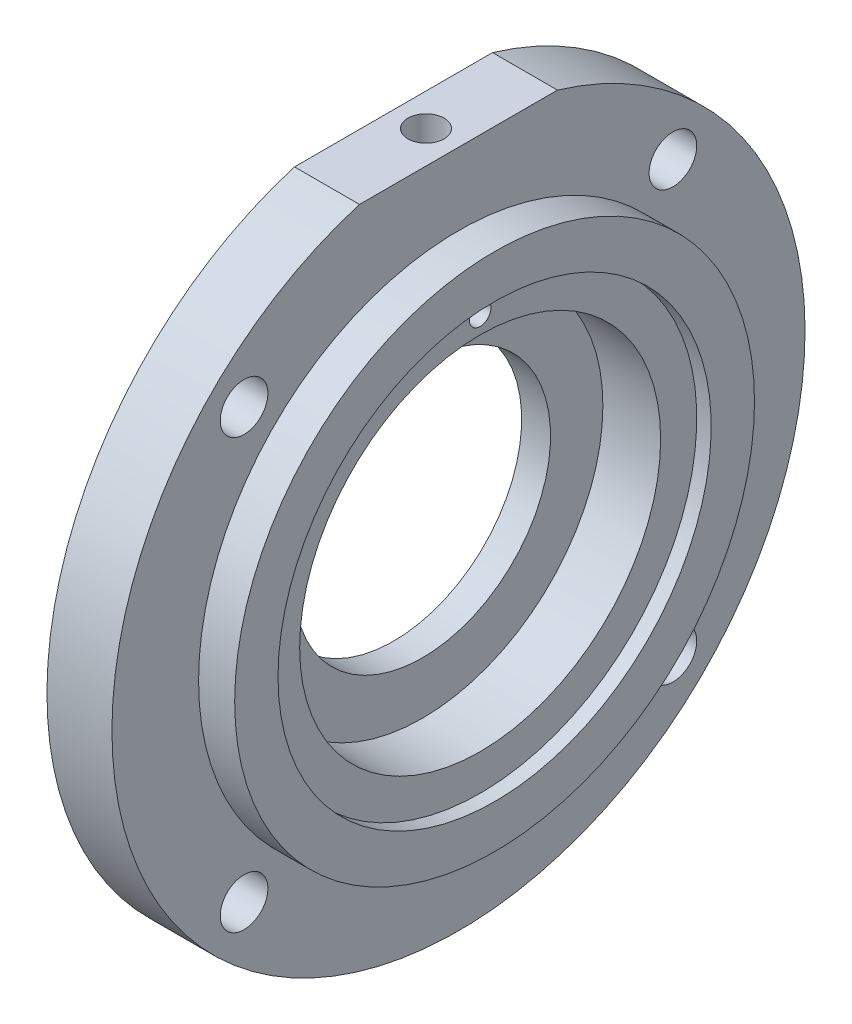
SolidWorks part; units mm, degrees
ref_plane "Front Plane" through (0, 0, 0) normal (0, 0, 1) x (1, 0, 0)
ref_plane "Top Plane" through (0, 0, 0) normal (0, 1, 0) x (1, 0, 0)
ref_plane "Right Plane" through (0, 0, 0) normal (1, 0, 0) x (0, 0, -1)
sketch "Sketch1" plane through (0, 0, 0) normal (0, 0, 1) x (1, 0, 0)
  line L0 (0, 0) -> (14, 0) construction
  line L1 (0, 48) -> (0, 17.75)
  line L2 (0, 17.75) -> (4, 17.75)
  line L3 (4, 17.75) -> (4, 25)
  line L4 (4, 25) -> (12, 25)
  line L5 (12, 25) -> (12, 30)
  line L6 (12, 30) -> (14, 30)
  line L7 (14, 30) -> (14, 36)
  line L8 (14, 36) -> (9, 36)
  line L9 (9, 36) -> (9, 48)
  line L10 (9, 48) -> (0, 48)
  point P13 (0, 0)
  point P15 (0, 55.9334)
  dimension "D1" = 14
  dimension "D2" = 35.5
  dimension "D3" = 4
  dimension "D4" = 2
  dimension "D5" = 5
  dimension "D6" = 50
  dimension "D7" = 60
  dimension "D8" = 72
  dimension "D9" = 96
revolve "Revolve1" add sketch "Sketch1" angle 360 about L0
sketch "Sketch2" plane through (0, 0, 0) normal (1, 0, 0) x (0, 0, -1)
  line L1 (-13.7113, 48) -> (13.7113, 48)
  line L2 (-13.7113, 48) -> (-13.7113, 46)
  line L3 (-13.7113, 46) -> (13.7113, 46)
  line L4 (13.7113, 48) -> (13.7113, 46)
  circle A0 centre (0, 0) radius 48 construction
  point P5 (0, 48)
  point P6 (0, 0)
  dimension "D1" = 46
extrude "Cut-Extrude1" cut sketch "Sketch2" along normal through all
hole_wizard "M6x1.0 Tapped Hole1" positions "Sketch5" profile "Sketch6" tap size "M6x1.0" standard "ANSI Metric"
sketch "Sketch5" plane through (0, 46, 0) normal (0, 1, 0) x (1, 0, 0)
  line L0 (0, 0) -> (9, 0) construction
  line L1 (9, -13.7113) -> (9, 13.7113) construction
  point P0 (4.5, 0)
  point P8 (0, 0)
  point P9 (4.5, 0)
sketch "Sketch6" plane through (4.5, 46, 0) normal (1, 0, 0) x (0, 0, 1)
  line L0 (0, 0) -> (0, 8.5022)
  line L1 (0, 8.5022) -> (2.5, 7)
  line L2 (2.5, 7) -> (2.5, 0)
  line L5 (2.5, 0) -> (0, 0)
  line L10 (0, 8.5022) -> (-2.5, 7) construction
  line L11 (0, -6.35) -> (0, 107.95) construction
  dimension "Tap Drill Dia." = 5
  dimension "Tap Drill Depth" = 7
  dimension "Drill Angle" = 118
cosmetic thread "Hole Thread1" parameters "D1"=20, "D2"=6
cosmetic thread "Hole Thread2" parameters "D1"=20, "D2"=6
hole_wizard "Ø3.0mm Dowel Hole1" positions "Sketch8" profile "Sketch9" hole size "Ø3.0" standard "ANSI Metric"
sketch "Sketch8" plane through (14, 0, 0) normal (1, 0, 0) x (0, 0, -1)
  line L0 (0, 25) -> (0, 30) construction
  circle A0 centre (0, 0) radius 25 construction
  circle A1 centre (0, 0) radius 25 construction
  circle A2 centre (0, 0) radius 30 construction
  point P0 (0, 27.5)
  point P13 (0, 27.5)
sketch "Sketch9" plane through (14, 27.5, 0) normal (0, 1, 0) x (0, 0, -1)
  line L0 (0, 0) -> (0, 11.9013)
  line L1 (0, 11.9013) -> (1.5, 11)
  line L2 (1.5, 11) -> (1.5, 0)
  line L5 (1.5, 0) -> (0, 0)
  line L10 (0, 11.9013) -> (-1.5, 11) construction
  line L11 (0, -6.35) -> (0, 107.95) construction
  dimension "Hole Dia." = 3
  dimension "Hole Depth" = 11
  dimension "Drill Angle" = 118
hole_wizard "Ø3.0mm Dowel Hole3" positions "Sketch13" profile "Sketch15" hole size "Ø3.0" standard "ISO"
sketch "Sketch13" plane through (0, 46, 0) normal (0, 1, 0) x (1, 0, 0)
  point P0 (4.5, 0)
sketch "Sketch15" plane through (4.5, 46, 0) normal (1, 0, 0) x (0, 0, 1)
  line L0 (0, 0) -> (0, 19.4003)
  line L1 (0, 19.4003) -> (1.5, 18.499)
  line L2 (1.5, 18.499) -> (1.5, 0)
  line L5 (1.5, 0) -> (0, 0)
  line L10 (0, 19.4003) -> (-1.5, 18.499) construction
  line L11 (0, -6.35) -> (0, 107.95) construction
  dimension "Hole Dia." = 3
  dimension "Hole Depth" = 18.499
  dimension "Drill Angle" = 118
sketch "Sketch16" plane through (9, 0, 0) normal (1, 0, 0) x (0, 0, -1)
  line L0 (0, 0) -> (0, 42) construction
  line L1 (0, 0) -> (-29.6985, 29.6985) construction
  circle A0 centre (0, 0) radius 42 construction
  circle A1 centre (-29.6985, 29.6985) radius 3.3
  dimension "D1" = 84
  dimension "D3" = 6.6
  dimension "D2" = 45
extrude "Cut-Extrude2" cut sketch "Sketch16" against normal through all
pattern_circular "CirPattern1" count 4 over 360 about axis through (0, 0, 0) along (1, 0, 0) of "Cut-Extrude2"
